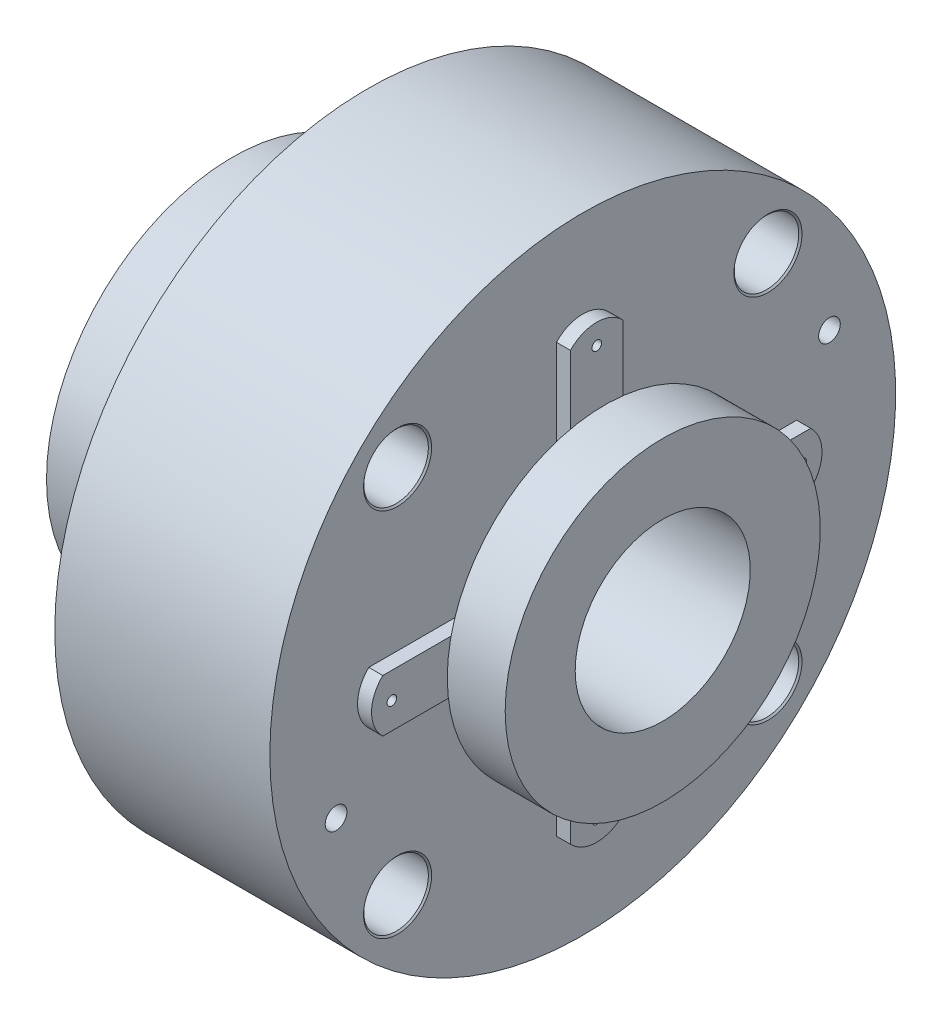
SolidWorks part; units mm, degrees
material "CD4Mc-U Duplex Stainless Steel"
ref_plane "Front Plane" through (0, 0, 0) normal (0, 0, 1) x (1, 0, 0)
ref_plane "Top Plane" through (0, 0, 0) normal (0, 1, 0) x (1, 0, 0)
ref_plane "Right Plane" through (0, 0, 0) normal (1, 0, 0) x (0, 0, -1)
sketch "Sketch1" plane through (0, 0, 0) normal (0, 0, 1) x (1, 0, 0)
  line L0 (-77.0583, 0) -> (72.901, 0) construction
  line L1 (-75.2766, 31.75) -> (-75.2766, 67.5005)
  line L2 (-75.2766, 67.5005) -> (-26.28, 67.5005)
  line L3 (-26.28, 67.5005) -> (-26.28, 113.4999)
  line L4 (-26.28, 113.4999) -> (51.7234, 113.4999)
  line L5 (51.7234, 113.4999) -> (51.7234, 53.34)
  line L6 (59.7302, 57.15) -> (80.7302, 57.15)
  line L7 (80.7302, 57.15) -> (80.7302, 31.75)
  line L8 (80.7302, 31.75) -> (-75.2766, 31.75)
  line L9 (59.7302, 57.15) -> (59.7302, 36.2689)
  line L10 (59.7302, 36.2689) -> (51.7234, 36.2689)
  line L11 (51.7234, 36.2689) -> (51.7234, 53.34)
  dimension "D1" = 48.9966
  dimension "D2" = 78.0034
  dimension "D3" = 107.0102
  dimension "D4" = 113.4999
  dimension "D5" = 31.75
  dimension "D6" = 67.5005
  dimension "D7" = 57.15
  dimension "D8" = 21
revolve "Revolve1" add sketch "Sketch1" angle 360 about L0
sketch "Sketch2" plane through (51.7234, 0, 0) normal (1, 0, 0) x (0, 0, -1)
  line L0 (0, 0) -> (0, 6.7702) construction
  line L2 (-9.5478, 6.7702) -> (-9.5478, 9.5478)
  line L4 (9.5022, 69.2007) -> (9.5022, 77.5973)
  line L5 (-9.5478, 69.1944) -> (-9.5478, 40.3346)
  line L6 (-9.5478, 77.5973) -> (0, 42.0991) construction
  line L7 (-9.5478, 40.3346) -> (9.5022, 40.3346)
  line L8 (-9.5478, 69.1944) -> (-9.5478, 77.5973)
  line L9 (0, 6.7702) -> (9.5022, 6.7702)
  line L10 (0, 42.0991) -> (0, 123.7737) construction
  line L11 (-0.0228, 42.1838) -> (9.5022, 77.5973) construction
  line L12 (-9.5478, 9.5478) -> (-98.4508, 98.4508) construction
  line L13 (9.5022, 40.3346) -> (9.5022, 69.2007)
  circle A1 centre (0, 0) radius 69.85 construction
  circle A2 centre (0, 0) radius 94.996 construction
  circle A3 centre (-67.1723, 67.1723) radius 12.0015
  arc A4 (9.5022, 77.5973) -> (-9.5478, 77.5973) centre (-0.0228, 68.5703) ccw
  circle A5 centre (0, 74.3337) radius 1.7259
  point P0 (-0.0228, 42.1838)
  dimension "D2" = 139.7
  dimension "D3" = 189.992
  dimension "D5" = 24.003
  dimension "D1" = 19.05
extrude "Boss-Extrude1" add sketch "Sketch2" along normal blind 5.08 contours L4 A4 L8 L5 L7 L13 A5
pattern_circular "CirPattern1" count 4 over 360 about axis through (0, 0, 0) along (1, 0, 0) of "Boss-Extrude1"
hole_wizard "Tap Drill for 1-12 Tap1" positions "3DSketch1" profile "Sketch3" hole size "1-12" standard "ANSI Inch" end condition through all
sketch3d "3DSketch1"
  point P0 (51.7234, 67.1723, 67.1723)
sketch "Sketch3" plane through (51.7234, 67.1723, 67.1723) normal (0, 1, 0) x (0, 0, -1)
  line L0 (0, 0) -> (0, 127)
  line L1 (0, 127) -> (11.7081, 127)
  line L2 (11.7081, 127) -> (11.7081, 0.5328)
  line L3 (11.7081, 0.5328) -> (12.3431, 0)
  line L5 (12.3431, 0) -> (0, 0)
  line L6 (-11.7081, 0.5328) -> (-12.3431, 0) construction
  line L11 (0, -6.35) -> (0, 107.95) construction
  dimension "Thru Hole Dia." = 23.4163
  dimension "Thru Hole Depth" = 127
  dimension "Near C'Sink Dia." = 24.6863
  dimension "Near C'Sink Angle" = 100
pattern_circular "CirPattern2" count 4 over 360 about axis through (0, 0, 0) along (1, 0, 0) of "Tap Drill for 1-12 Tap1"
sketch "Sketch4" plane through (51.7234, 0, 0) normal (1, 0, 0) x (0, 0, -1)
  circle A0 centre (0, 0) radius 94.996 construction
  circle A1 centre (-89.4812, -31.896) radius 3.9274
  dimension "D1" = 189.992
extrude "Cut-Extrude1" cut sketch "Sketch4" against normal through all
pattern_circular "CirPattern3" count 2 over 360 about axis through (0, 0, 0) along (1, 0, 0) of "Cut-Extrude1"
